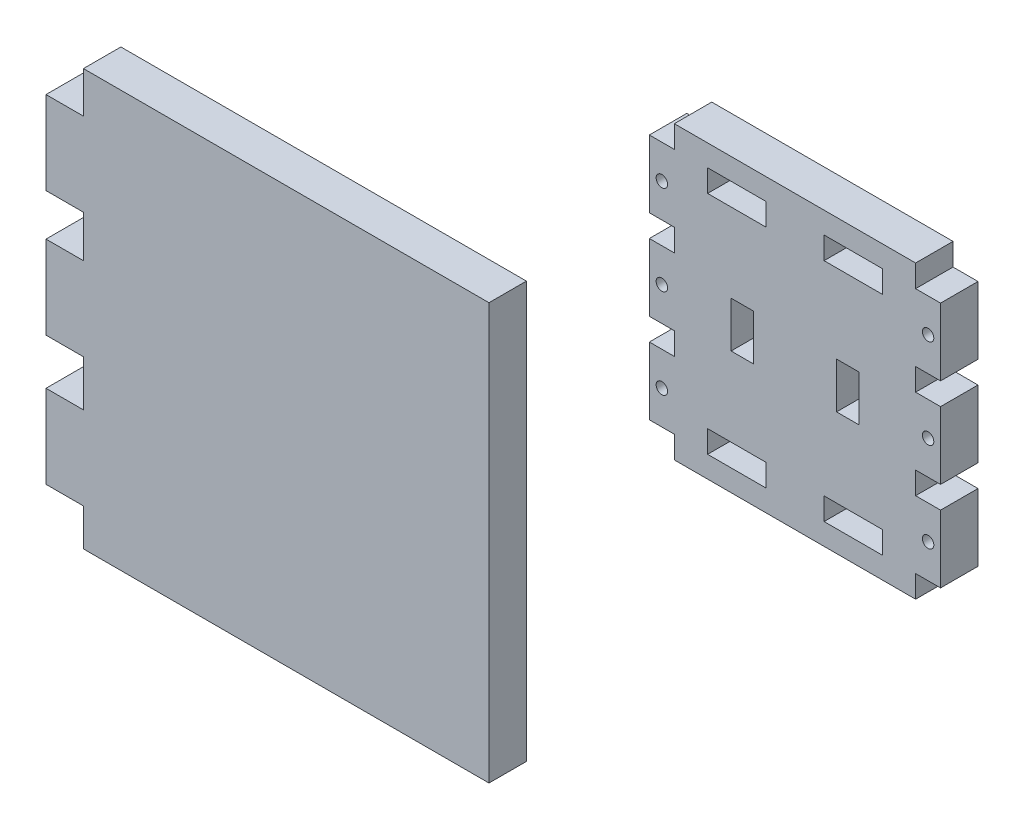
SolidWorks part; units mm, degrees
ref_plane "Front Plane" through (0, 0, 0) normal (0, 0, 1) x (1, 0, 0)
ref_plane "Top Plane" through (0, 0, 0) normal (0, 1, 0) x (1, 0, 0)
ref_plane "Right Plane" through (0, 0, 0) normal (1, 0, 0) x (0, 0, -1)
sketch "Model" plane through (0, 0, 0) normal (0, 0, 1) x (1, 0, 0)
  line L0 (122.2964, 159.5451) -> (122.2964, 89.5451) construction
  line L1 (93.2964, 89.5451) -> (151.2964, 89.5451)
  line L2 (93.2964, 89.5451) -> (93.2964, 94.8951)
  line L3 (93.2964, 159.5451) -> (151.2964, 159.5451)
  line L4 (151.2964, 89.5451) -> (151.2964, 94.8951)
  line L5 (151.2964, 124.5451) -> (75.8907, 124.5451) construction
  line L6 (90.2964, 154.1951) -> (90.2964, 137.9951) construction
  line L7 (101.2964, 154.3751) -> (115.2964, 154.3751)
  line L8 (101.2964, 154.3751) -> (101.2964, 149.0251)
  line L9 (101.2964, 149.0251) -> (115.2964, 149.0251)
  line L10 (115.2964, 154.3751) -> (115.2964, 149.0251)
  line L11 (93.2964, 154.1951) -> (87.2964, 154.1951)
  line L12 (157.2964, 146.0951) -> (151.2964, 146.0951) construction
  line L13 (93.2964, 137.9951) -> (87.2964, 137.9951)
  line L14 (87.2964, 154.1951) -> (87.2964, 137.9951)
  line L15 (87.2964, 146.0951) -> (93.2964, 146.0951) construction
  line L16 (93.2964, 154.1951) -> (93.2964, 159.5451)
  line L17 (154.2964, 154.1951) -> (154.2964, 137.9951) construction
  line L18 (157.2964, 154.1951) -> (157.2964, 137.9951)
  line L19 (151.2964, 137.9951) -> (157.2964, 137.9951)
  line L20 (151.2964, 154.1951) -> (157.2964, 154.1951)
  line L21 (129.2964, 154.3751) -> (129.2964, 149.0251)
  line L22 (143.2964, 149.0251) -> (129.2964, 149.0251)
  line L23 (143.2964, 154.3751) -> (143.2964, 149.0251)
  line L24 (143.2964, 154.3751) -> (129.2964, 154.3751)
  line L25 (154.2964, 94.8951) -> (154.2964, 111.0951) construction
  line L26 (87.2964, 102.9951) -> (93.2964, 102.9951) construction
  line L27 (157.2964, 102.9951) -> (151.2964, 102.9951) construction
  line L28 (90.2964, 94.8951) -> (90.2964, 111.0951) construction
  line L29 (143.2964, 94.7151) -> (129.2964, 94.7151)
  line L30 (143.2964, 94.7151) -> (143.2964, 100.0651)
  line L31 (143.2964, 100.0651) -> (129.2964, 100.0651)
  line L32 (129.2964, 94.7151) -> (129.2964, 100.0651)
  line L33 (151.2964, 94.8951) -> (157.2964, 94.8951)
  line L34 (151.2964, 111.0951) -> (157.2964, 111.0951)
  line L35 (157.2964, 94.8951) -> (157.2964, 111.0951)
  line L36 (87.2964, 94.8951) -> (87.2964, 111.0951)
  line L37 (93.2964, 111.0951) -> (87.2964, 111.0951)
  line L38 (93.2964, 94.8951) -> (87.2964, 94.8951)
  line L39 (115.2964, 94.7151) -> (115.2964, 100.0651)
  line L40 (101.2964, 100.0651) -> (115.2964, 100.0651)
  line L41 (101.2964, 94.7151) -> (101.2964, 100.0651)
  line L42 (101.2964, 94.7151) -> (115.2964, 94.7151)
  line L43 (93.2964, 111.0951) -> (93.2964, 116.4451)
  line L44 (151.2964, 111.0951) -> (151.2964, 116.4451)
  line L45 (151.2964, 154.1951) -> (151.2964, 159.5451)
  line L46 (87.2964, 124.5451) -> (93.2964, 124.5451) construction
  line L47 (93.2964, 132.6451) -> (87.2964, 132.6451)
  line L48 (137.6464, 130.0451) -> (132.2964, 119.0451) construction
  line L49 (93.2964, 116.4451) -> (87.2964, 116.4451)
  line L50 (87.2964, 132.6451) -> (87.2964, 116.4451)
  line L51 (90.2964, 132.6451) -> (90.2964, 116.4451) construction
  line L52 (93.2964, 132.6451) -> (93.2964, 137.9951)
  line L53 (106.9464, 119.0451) -> (112.2964, 119.0451)
  line L54 (106.9464, 119.0451) -> (106.9464, 130.0451)
  line L55 (106.9464, 130.0451) -> (112.2964, 130.0451)
  line L56 (112.2964, 119.0451) -> (112.2964, 130.0451)
  line L57 (106.9464, 119.0451) -> (112.2964, 130.0451) construction
  line L58 (106.9464, 130.0451) -> (112.2964, 119.0451) construction
  line L59 (137.6464, 119.0451) -> (132.2964, 130.0451) construction
  line L60 (154.2964, 132.6451) -> (154.2964, 116.4451) construction
  line L61 (157.2964, 124.5451) -> (151.2964, 124.5451) construction
  line L62 (132.2964, 119.0451) -> (132.2964, 130.0451)
  line L63 (137.6464, 130.0451) -> (132.2964, 130.0451)
  line L64 (137.6464, 119.0451) -> (137.6464, 130.0451)
  line L65 (137.6464, 119.0451) -> (132.2964, 119.0451)
  line L66 (157.2964, 132.6451) -> (157.2964, 116.4451)
  line L67 (151.2964, 116.4451) -> (157.2964, 116.4451)
  line L68 (151.2964, 132.6451) -> (157.2964, 132.6451)
  line L69 (151.2964, 132.6451) -> (151.2964, 137.9951)
  line L70 (-48.7431, 90.0901) -> (-57.7431, 90.0901)
  line L71 (-48.7431, 0) -> (48.7431, 0)
  line L72 (-48.7431, 0) -> (-48.7431, 8.9435)
  line L73 (-48.7431, 100) -> (48.7431, 100)
  line L74 (48.7431, 0) -> (48.7431, 100)
  line L75 (0, 0) -> (0, 100) construction
  line L76 (-48.7431, 60) -> (-48.7431, 70.0901)
  line L77 (-48.7431, 60) -> (-57.7431, 60)
  line L78 (-48.7431, 28.9435) -> (-48.7431, 40)
  line L79 (-48.7431, 40) -> (-57.7431, 40)
  line L80 (-57.7431, 60) -> (-57.7431, 40)
  line L81 (-48.7431, 70.0901) -> (-57.7431, 70.0901)
  line L82 (-57.7431, 90.0901) -> (-57.7431, 70.0901)
  line L83 (-48.7431, 28.9435) -> (-57.7431, 28.9435)
  line L84 (0, 50) -> (-57.7431, 50) construction
  line L85 (-48.7431, 8.9435) -> (-57.7431, 8.9435)
  line L86 (-57.7431, 28.9435) -> (-57.7431, 8.9435)
  line L87 (-48.7431, 90.0901) -> (-48.7431, 100)
  circle A1 centre (90.2964, 146.0951) radius 1.375
  circle A6 centre (154.2964, 146.0951) radius 1.375
  circle A7 centre (154.2964, 102.9951) radius 1.375
  circle A8 centre (90.2964, 102.9951) radius 1.375
  circle A9 centre (90.2964, 124.5451) radius 1.375
  circle A10 centre (154.2964, 124.5451) radius 1.375
  point P84 (109.6214, 124.5451)
  point P102 (134.9714, 124.5451)
  dimension "D23" = 2.75
  dimension "D2" = 58
  dimension "D8" = 5.35
  dimension "D10" = 14
  dimension "D12" = 5.17
  dimension "D14" = 8
  dimension "D19" = 5.35
  dimension "D22" = 5.35
  dimension "D24" = 6
  dimension "D25" = 16.2
  dimension "D26" = 5.35
  dimension "D27" = 11
  dimension "D30" = 13.65
  dimension "D6" = 9
  dimension "D7" = 100
  dimension "D9" = 20
  dimension "D4" = 2
  dimension "D5" = 2
extrude "Boss-Extrude1" add sketch "Model" along normal blind 9
equation "\"material-thickness\" = 9mm"
equation "\"tab-width-large\" = 30mm ' Width of the large version of the Tab"
equation "\"tab-width-small\" = 20mm ' Width of the small version of the Tab"
equation "\"mdfthick\"=5.35"
equation "\"D26@Model\"=\"mdfthick\""
equation "\"D8@Model\"=\"mdfthick\""
equation "\"D19@Model\"=\"mdfthick\""
equation "\"D1@Boss-Extrude1\"=\"material-thickness\""
equation "\"D6@Model\"=\"material-thickness\""
equation "\"D9@Model\"=\"tab-width-small\""
